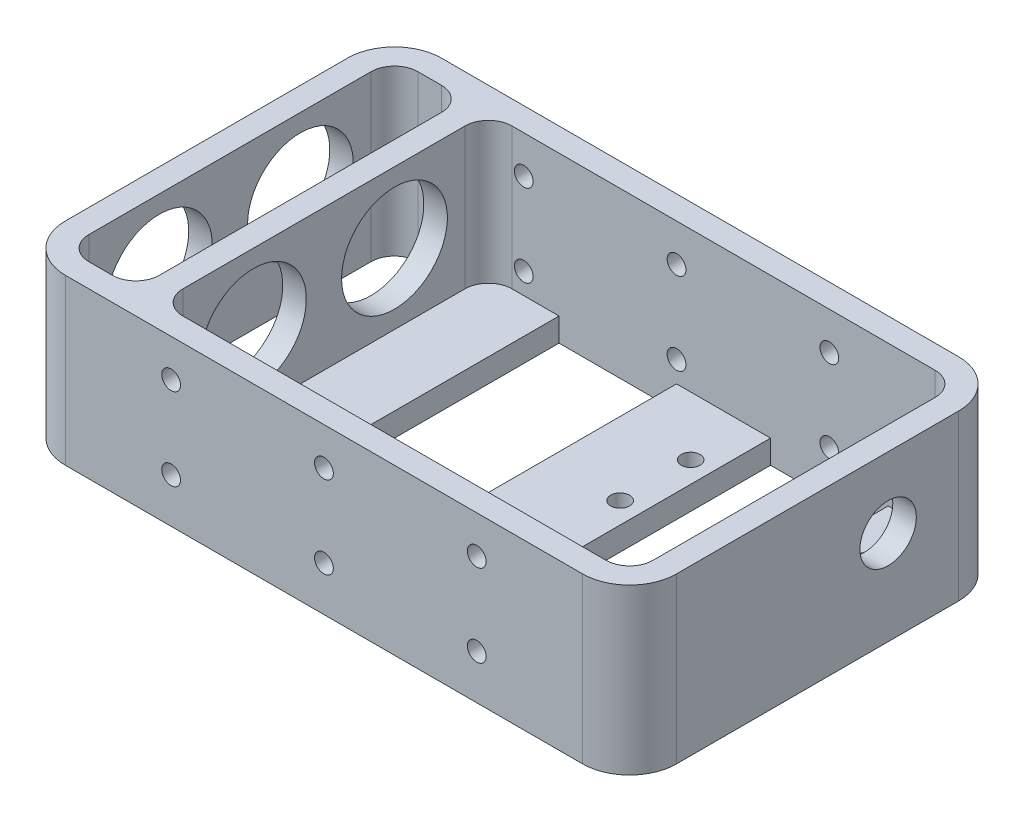
SolidWorks part; units mm, degrees
ref_plane "Front Plane" through (0, 0, 0) normal (0, 0, 1) x (1, 0, 0)
ref_plane "Top Plane" through (0, 0, 0) normal (0, 1, 0) x (1, 0, 0)
ref_plane "Right Plane" through (0, 0, 0) normal (1, 0, 0) x (0, 0, -1)
sketch "Sketch1" plane through (0, 0, 0) normal (0, 1, 0) x (1, 0, 0)
  line L0 (-76.2, -44.45) -> (57.15, -44.45)
  line L1 (-82.55, -50.8) -> (82.55, -50.8)
  line L2 (-82.55, -50.8) -> (-82.55, 50.8)
  line L3 (-82.55, 50.8) -> (82.55, 50.8)
  line L4 (82.55, -50.8) -> (82.55, 50.8)
  line L5 (-82.55, -50.8) -> (82.55, 50.8) construction
  line L6 (-82.55, 50.8) -> (82.55, -50.8) construction
  line L7 (57.15, -44.45) -> (57.15, 44.45)
  line L8 (-76.2, 44.45) -> (57.15, 44.45)
  line L9 (-76.2, -44.45) -> (-76.2, 44.45)
  line L10 (-57.15, 44.45) -> (-57.15, -44.45)
  line L11 (-31.75, 44.45) -> (-31.75, -44.45)
  line L12 (0, 44.45) -> (0, -44.45)
  line L13 (25.4, -44.45) -> (25.4, 44.45)
  line L14 (-50.8, 44.45) -> (-50.8, -44.45) construction
  line L15 (76.2, 44.45) -> (76.2, -44.45) construction
  line L16 (57.15, -44.45) -> (82.55, -44.45) construction
  line L17 (57.15, 44.45) -> (82.55, 44.45) construction
  line L18 (76.2, 0) -> (57.15, 0) construction
  line L19 (66.675, 0) -> (66.675, 44.45) construction
  line L20 (-50.8, 0) -> (-31.75, 0) construction
  line L21 (-41.275, 0) -> (-41.275, -44.45) construction
  circle A0 centre (66.675, 28.575) radius 2.54
  circle A1 centre (66.675, 9.525) radius 2.54
  circle A2 centre (19.685, 28.575) radius 2.54
  circle A3 centre (19.685, 9.525) radius 2.54
  circle A4 centre (5.715, -9.525) radius 2.54
  circle A5 centre (5.715, -28.575) radius 2.54
  circle A6 centre (-41.275, -9.525) radius 2.54
  circle A7 centre (-41.275, -28.575) radius 2.54
  point P0 (0, 0)
  dimension "D9" = 5.08
  dimension "D10" = 88.9
  dimension "D1" = 165.1
  dimension "D2" = 101.6
  dimension "D3" = 25.4
  dimension "D4" = 6.35
  dimension "D5" = 25.4
  dimension "D6" = 31.75
  dimension "D7" = 6.35
  dimension "D8" = 6.35
  dimension "D11" = 6.35
  dimension "D12" = 46.99
  dimension "D13" = 46.99
  dimension "D14" = 19.05
  dimension "D15" = 31.75
  dimension "D16" = 19.05
  dimension "D17" = 19.05
  dimension "D18" = 19.05
  dimension "D19" = 15.875
extrude "Mounting Base" add sketch "Sketch1" along normal blind 6.35 contours L0 L13 L8 L12 A5 A4 A3 A2 | L11 L8 L10 L0 A7 A6 | L1 L4 L3 L2 A1 A0 L0 L9 L8 L7
sketch "Sketch2" plane through (0, 6.35, 0) normal (0, 1, 0) x (1, 0, 0)
  line L0 (-76.2, -44.45) -> (76.2, -44.45)
  line L1 (-82.55, -50.8) -> (82.55, -50.8)
  line L2 (-82.55, -50.8) -> (-82.55, 50.8)
  line L3 (-82.55, 50.8) -> (82.55, 50.8)
  line L4 (82.55, -50.8) -> (82.55, 50.8)
  line L5 (-82.55, -50.8) -> (82.55, 50.8) construction
  line L6 (-82.55, 50.8) -> (82.55, -50.8) construction
  line L7 (76.2, -44.45) -> (76.2, 44.45)
  line L8 (-76.2, 44.45) -> (76.2, 44.45)
  line L9 (-76.2, -44.45) -> (-76.2, 44.45)
  line L10 (-57.15, 44.45) -> (-57.15, -44.45)
  line L11 (-50.8, -44.45) -> (-50.8, 44.45)
  point P0 (0, 0)
  line M1 (0, -44.45) -> (-31.75, -44.45)
  line M3 (-31.75, 44.45) -> (0, 44.45)
  line M5 (57.15, -44.45) -> (25.4, -44.45)
  line M7 (25.4, 44.45) -> (57.15, 44.45)
  line M13 (-57.15, 44.45) -> (-57.15, -44.45)
  line M14 (-57.15, -44.45) -> (-76.2, -44.45)
  line M15 (-76.2, -44.45) -> (-76.2, 44.45)
  line M16 (-76.2, 44.45) -> (-57.15, 44.45)
  line M19 (-82.55, -50.8) -> (82.55, -50.8)
  line M20 (82.55, -50.8) -> (82.55, 50.8)
  line M21 (82.55, 50.8) -> (-82.55, 50.8)
  line M22 (-82.55, 50.8) -> (-82.55, -50.8)
  dimension "D2" = 6.35
  dimension "D1" = 6.35
extrude "Walls" add sketch "Sketch2" along normal blind 38.1 contours L0 L11 L8 M13 | L8 L7 L0 M22 M19 M20 M21 M16 M3 M7 M5 M1 M14 M15
sketch "Sketch3" plane through (-82.55, 0, 0) normal (-1, 0, 0) x (0, 0, 1)
  line L0 (-50.8, 44.45) -> (-50.8, 0) construction
  line L1 (-50.8, 25.4) -> (50.8, 25.4) construction
  line L2 (50.8, 44.45) -> (50.8, 0) construction
  line L3 (-50.8, 22.225) -> (50.8, 22.225) construction
  circle A0 centre (-19.05, 25.4) radius 14.2875
  circle A1 centre (19.05, 25.4) radius 14.2875
  dimension "D2" = 3.175
  dimension "D5" = 28.575
  dimension "D3" = 38.1
  dimension "D4" = 31.75
extrude "Bearing Holes" cut sketch "Sketch3" against normal blind 38.1
sketch "Sketch4" plane through (82.55, 0, 0) normal (1, 0, 0) x (0, 0, -1)
  line L0 (-50.8, 22.225) -> (50.8, 22.225) construction
  line L1 (-50.8, 44.45) -> (-50.8, 0) construction
  line L2 (50.8, 44.45) -> (50.8, 0) construction
  line L3 (-50.8, 25.4) -> (50.8, 25.4) construction
  circle A0 centre (19.05, 25.4) radius 7.62
  dimension "D3" = 15.24
  dimension "D1" = 3.175
  dimension "D2" = 31.75
extrude "Shaft Holes" cut sketch "Sketch4" against normal blind 38.1
sketch "Sketch5" plane through (0, 0, -50.8) normal (0, 0, -1) x (-1, 0, 0)
  line L0 (0, 22.225) -> (0, 44.45) construction
  line L2 (-41.275, 22.225) -> (-82.55, 22.225) construction
  line L3 (41.275, 44.45) -> (41.275, 22.225) construction
  line L4 (82.55, 0) -> (-82.55, 0) construction
  line L5 (-82.55, 44.45) -> (-82.55, 0) construction
  line L6 (-41.275, 44.45) -> (-41.275, 22.225) construction
  line L7 (0, 22.225) -> (41.275, 22.225) construction
  line L8 (-41.275, 22.225) -> (0, 22.225) construction
  line L9 (0, 22.225) -> (0, 0) construction
  line L10 (-82.55, 44.45) -> (82.55, 44.45) construction
  line L11 (-41.275, 22.225) -> (-41.275, 0) construction
  line L12 (41.275, 22.225) -> (82.55, 22.225) construction
  line L13 (82.55, 44.45) -> (82.55, 0) construction
  line L14 (41.275, 22.225) -> (41.275, 0) construction
  circle A0 centre (-41.275, 34.29) radius 2.54
  circle A1 centre (-41.275, 12.065) radius 2.54
  circle A2 centre (41.275, 34.29) radius 2.54
  circle A3 centre (41.275, 12.065) radius 2.54
  circle A4 centre (0, 34.29) radius 2.54
  circle A5 centre (0, 12.065) radius 2.54
  dimension "D2" = 5.08
  dimension "D1" = 10.16
  dimension "D3" = 10.16
extrude "Mod Holes" cut sketch "Sketch5" against normal through all
fillet "Outside Vertices" radius 12.7 4 edges at (-82.55, 22.225, -50.8) (-82.55, 22.225, 50.8) (82.55, 22.225, -50.8) (82.55, 22.225, 50.8)
sketch "Sketch6" plane through (0, 0, 0) normal (0, -1, 0) x (1, 0, 0)
  line L0 (0, -44.45) -> (0, 44.45) construction
  line L1 (-82.55, -50.8) -> (82.55, -50.8)
  line L2 (-82.55, -50.8) -> (-82.55, 50.8)
  line L3 (-82.55, 50.8) -> (82.55, 50.8)
  line L4 (82.55, -50.8) -> (82.55, 50.8)
  line L5 (-82.55, -50.8) -> (82.55, 50.8) construction
  line L6 (-82.55, 50.8) -> (82.55, -50.8) construction
  circle A0 centre (82.55, 50.8) radius 9.525
  circle A1 centre (82.55, -50.8) radius 9.525
  circle A2 centre (-82.55, -50.8) radius 9.525
  circle A3 centre (-82.55, 50.8) radius 9.525
  point P8 (0, 0)
  arc M20 (-82.55, -38.1) -> (-69.85, -50.8) centre (-69.85, -38.1) ccw
  arc M22 (69.85, -50.8) -> (82.55, -38.1) centre (69.85, -38.1) ccw
  arc M24 (82.55, 38.1) -> (69.85, 50.8) centre (69.85, 38.1) ccw
  arc M26 (-69.85, 50.8) -> (-82.55, 38.1) centre (-69.85, 38.1) ccw
  dimension "D3" = 19.05
  dimension "D1" = 101.6
  dimension "D2" = 165.1
extrude "Mouse Ears" [suppressed] add sketch "Sketch6" against normal blind 1.27 contours L3 A3 L2 | L3 L2 M26 | L4 L3 M24 | L4 A0 L3 | L1 A1 L4 | L1 L4 M22 | L2 L1 M20 | L2 A2 L1
fillet "Inside Vertices" radius 6.35 8 edges at (-76.2, 22.225, 44.45) (-76.2, 22.225, -44.45) (76.2, 25.4, 44.45) (76.2, 25.4, -44.45) (-50.8, 25.4, -44.45) (-50.8, 25.4, 44.45) (-57.15, 22.225, 44.45) (-57.15, 22.225, -44.45)
